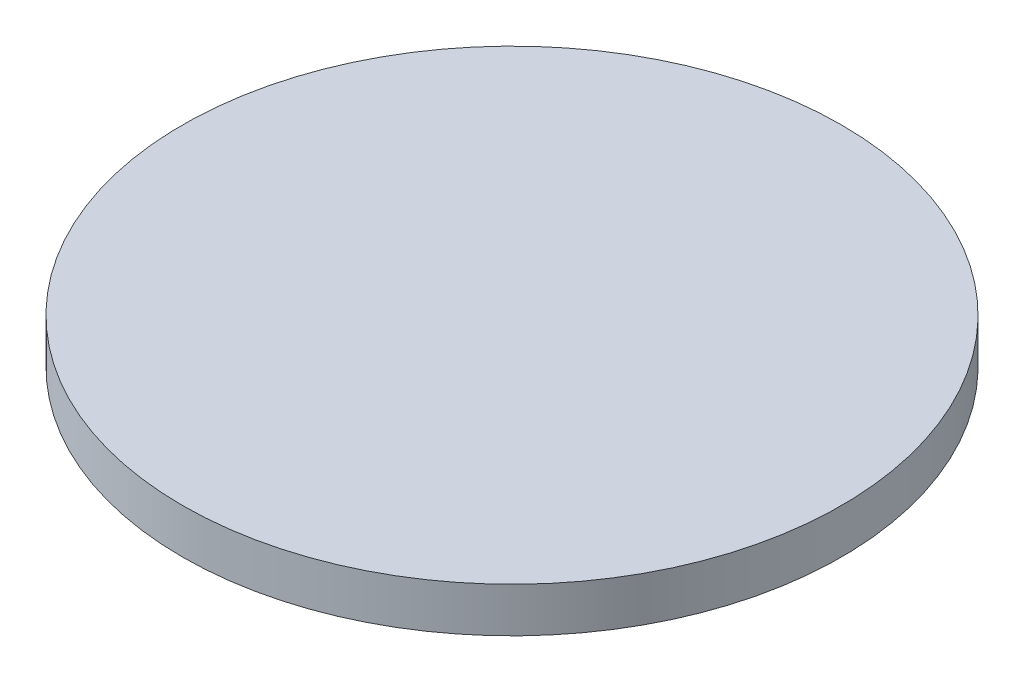
SolidWorks part; units mm, degrees
material "6061-T6 (SS)"
ref_plane "Front Plane" through (0, 0, 0) normal (0, 0, 1) x (1, 0, 0)
ref_plane "Top Plane" through (0, 0, 0) normal (0, 1, 0) x (1, 0, 0)
ref_plane "Right Plane" through (0, 0, 0) normal (1, 0, 0) x (0, 0, -1)
sketch "Sketch1" plane through (0, 0, 0) normal (0, 1, 0) x (1, 0, 0)
  line L5 (0, 0) -> (127.635, 0)
  line L6 (0, 0) -> (0, 127.635)
  line L7 (0, 127.635) -> (127.635, 127.635)
  line L8 (127.635, 0) -> (127.635, 127.635)
  dimension "D1" = 127.635
  dimension "D2" = 127.635
extrude "Boss-Extrude1" add sketch "Sketch1" along normal blind 9.525 contours L5 L8 L7 L6
sketch "Sketch13" plane through (0, 9.525, 0) normal (0, 1, 0) x (1, 0, 0)
  circle A0 centre (63.8175, 63.8175) radius 93.6625
  dimension "D1" = 187.325
extrude "Boss-Extrude2" add sketch "Sketch13" against normal blind 12.7 contours A0
sketch "Sketch6" [suppressed] plane through (127.635, 0, 0) normal (1, 0, 0) x (0, 0, -1)
  circle A0 centre (4.7625, 4.7625) radius 1.3526
  dimension "D1" = 2.7051
extrude "6-32 hole1" [suppressed] cut sketch "Sketch6" against normal blind 12.7
sketch "Sketch7" [suppressed] plane through (0, 0, -127.635) normal (0, 0, -1) x (-1, 0, 0)
  circle A0 centre (-122.8725, 4.7625) radius 1.3525
  dimension "D1" = 2.7051
sketch "Sketch8" [suppressed] plane through (0, 0, 0) normal (-1, 0, 0) x (0, 0, 1)
  circle A0 centre (-122.8725, 4.7625) radius 1.3525
  dimension "D1" = 2.7051
sketch "Sketch9" [suppressed] plane through (0, 0, 0) normal (0, 0, 1) x (1, 0, 0)
  circle A0 centre (4.7625, 4.7625) radius 1.3526
  dimension "D1" = 2.7051
sketch "Sketch5" plane through (0, 9.525, 0) normal (0, 1, 0) x (1, 0, 0)
  circle A0 centre (63.8175, 63.8175) radius 46.355
  circle A1 centre (63.8175, 63.8175) radius 93.6625 construction
  dimension "D1" = 92.71
extrude "Cut-Extrude1" [suppressed] cut sketch "Sketch5" against normal blind 9.525
sketch "Sketch11" [suppressed] plane through (0, 9.525, 0) normal (0, 1, 0) x (1, 0, 0)
  line L0 (63.8175, 63.8175) -> (63.8175, 115.443) construction
  circle A0 centre (63.8175, 115.443) radius 1.4351
  dimension "D2" = 2.8702
  dimension "D1" = 51.6255
extrude "Cut-Extrude3" [suppressed] cut sketch "Sketch11" against normal through all contours A0
pattern_circular "CirPattern1" [suppressed] count 12 over 360
sketch "Sketch12" [suppressed] plane through (0, 9.525, 0) normal (0, 1, 0) x (1, 0, 0)
  circle A0 centre (63.8175, 63.8175) radius 56.4198
  dimension "D1" = 112.8395
extrude "Cut-Extrude4" [suppressed] cut sketch "Sketch12" against normal blind 1.27
sketch "Sketch15" [suppressed] plane through (0, 9.525, 0) normal (0, 1, 0) x (1, 0, 0)
  line L0 (63.8175, 63.8175) -> (-29.845, 63.8175) construction
  line L1 (0, -39.1057) -> (0, 39.1057) construction
  line L2 (-20.0025, 63.8175) -> (-25.0825, 63.8175)
  line L3 (-8.7458, 105.7742) -> (-13.2051, 108.2104)
  line L4 (-8.7458, 105.7742) -> (-20.0025, 63.8175) construction
  circle A0 centre (63.8175, 63.8175) radius 56.4198 construction
  arc A1 (-20.0025, 63.8175) -> (-8.7458, 105.7742) centre (63.8175, 63.8175) cw
  arc A2 (-25.0825, 63.8175) -> (-13.2051, 108.2104) centre (63.8175, 63.8175) cw
  circle A3 centre (63.8175, 63.8175) radius 93.6625 construction
  point P0 (63.8175, 63.8175)
  point P11 (-14.3741, 84.7959)
  dimension "D1" = 46.482
  dimension "D2" = 88.9
  dimension "D3" = 83.82
  dimension "D4" = 43.942
sketch "Sketch16" plane through (0, 9.525, 0) normal (0, 1, 0) x (1, 0, 0)
  circle A0 centre (63.8175, 63.8175) radius 88.9
  circle A1 centre (63.8175, 63.8175) radius 85.725
  dimension "D1" = 177.8
  dimension "D2" = 171.45
extrude "Cut-Extrude5" [suppressed] cut sketch "Sketch16" against normal blind 7.62
sketch "Sketch18" [suppressed] plane through (0, 8.255, 0) normal (0, 1, 0) x (1, 0, 0)
  line L0 (63.8175, 185.7252) -> (63.8175, -48.6103) construction
ref_plane "Plane1" [suppressed] through (63.8175, 0, 0) normal (-1, 0, 0) x (0, 0, 1)
ref_plane "Plane2" [suppressed] through (0, 0, 29.845) normal (0, 0, 1) x (1, 0, 0)
sketch "Sketch17" [suppressed] plane through (0, 0, 29.845) normal (0, 0, 1) x (1, 0, 0)
  line L0 (63.8175, 103.0287) -> (63.8175, -103.0287) construction
  line L1 (157.48, 9.525) -> (-29.845, 9.525) construction
  circle A0 centre (63.8175, 5.715) radius 1.4351
  dimension "D1" = 2.8702
  dimension "D2" = 3.81
extrude "Cut-Extrude6" [suppressed] cut sketch "Sketch17" against normal blind 15.24
pattern_circular "CirPattern2" [suppressed] count 12 over 360
sketch "Sketch19" plane through (0, -3.175, 0) normal (0, -1, 0) x (1, 0, 0)
  circle A0 centre (63.8175, -63.8175) radius 25.4
  dimension "D1" = 50.8
extrude "Cut-Extrude7" [suppressed] cut sketch "Sketch19" against normal blind 87.63
